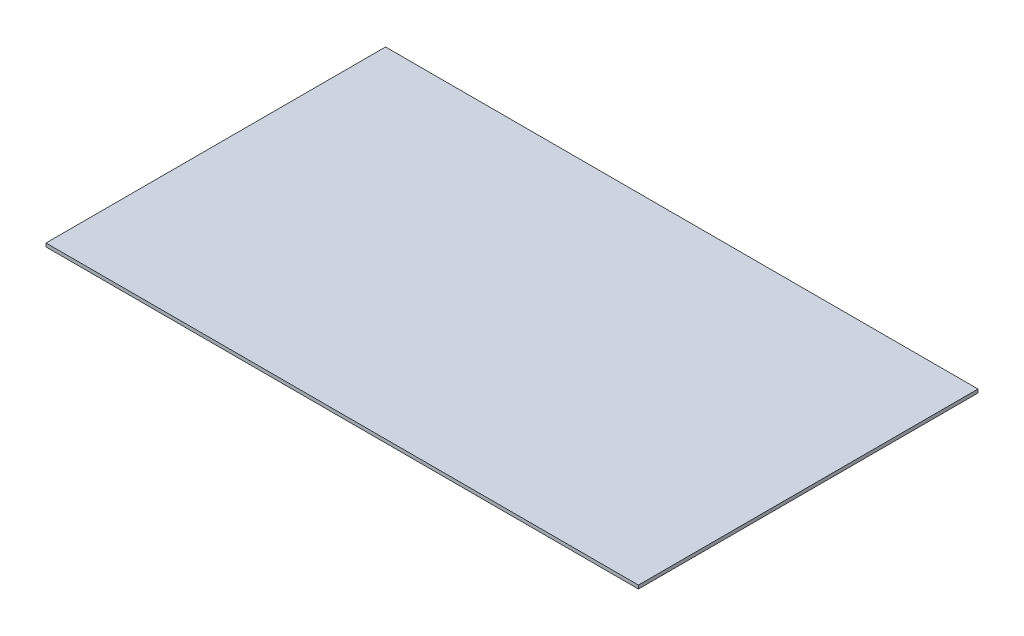
SolidWorks part; units mm, degrees
ref_plane "Front Plane" through (0, 0, 0) normal (0, 0, 1) x (1, 0, 0)
ref_plane "Top Plane" through (0, 0, 0) normal (0, 1, 0) x (1, 0, 0)
ref_plane "Right Plane" through (0, 0, 0) normal (1, 0, 0) x (0, 0, -1)
sketch "Sketch1" plane through (0, 0, 0) normal (0, 1, 0) x (1, 0, 0)
  line L1 (-58.6603, -616.7043) -> (1027.1897, -616.7043)
  line L2 (-58.6603, -616.7043) -> (-58.6603, -1239.0043)
  line L3 (-58.6603, -1239.0043) -> (1027.1897, -1239.0043)
  line L4 (1027.1897, -616.7043) -> (1027.1897, -1239.0043)
  dimension "D1" = 1085.85
  dimension "D2" = 622.3
extrude "Boss-Extrude1" add sketch "Sketch1" along normal blind 6.35
